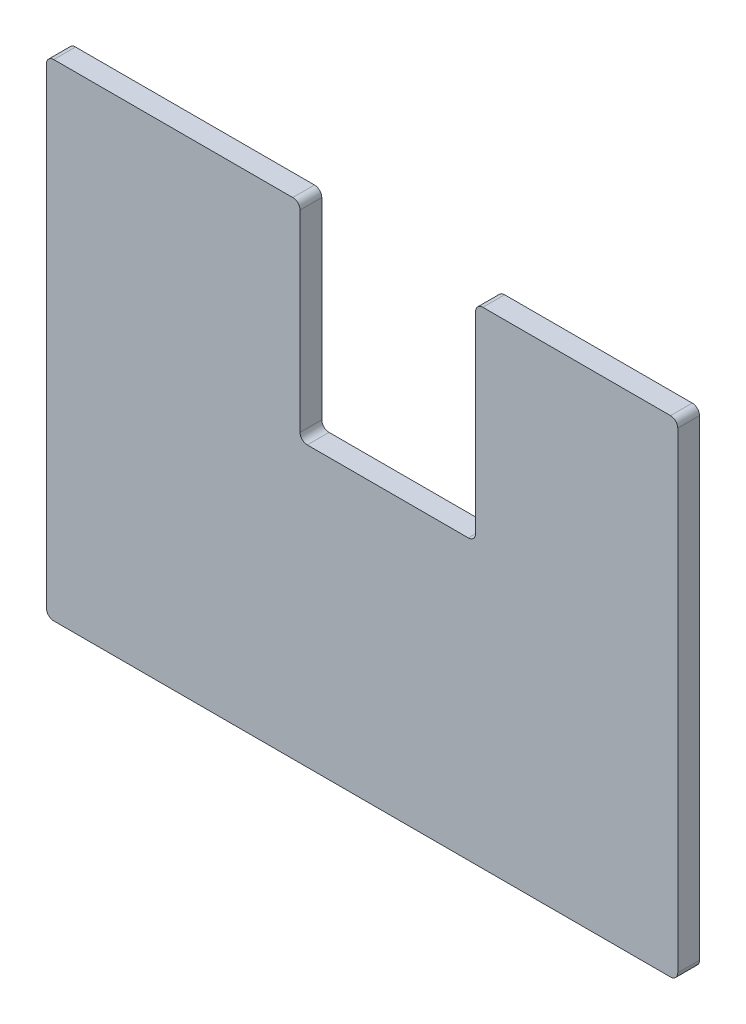
SolidWorks part; units mm, degrees
material "Faia"
ref_plane "Plano frontal" through (0, 0, 0) normal (0, 0, 1) x (1, 0, 0)
ref_plane "Plano superior" through (0, 0, 0) normal (0, 1, 0) x (1, 0, 0)
ref_plane "Plano direito" through (0, 0, 0) normal (1, 0, 0) x (0, 0, -1)
sketch "Esboço1" plane through (0, 0, 0) normal (0, 0, 1) x (1, 0, 0)
  line L0 (65.1024, 0) -> (-63.1564, 0) construction
  line L15 (-43.4857, -30.7684) -> (-43.4857, -35.6299) construction
  line L16 (-8.5074, 33.5098) -> (-43.4857, 33.5098)
  line L17 (43.6082, 33.5098) -> (15.7164, 33.5098)
  line L18 (43.6082, 33.5098) -> (43.6082, -33.5661)
  line L19 (43.6082, -33.5661) -> (-43.4857, -33.5661)
  line L20 (-43.4857, 33.5098) -> (-43.4857, -33.5661)
  line L22 (-8.5074, 33.5098) -> (-8.5074, 4.9536)
  line L23 (-8.5074, 4.9536) -> (15.7164, 4.9536)
  line L24 (15.7164, 33.5098) -> (15.7164, 4.9536)
  line L25 (0, 4.9536) -> (0, -59.4583) construction
extrude "Ressalto-extrusão1" add sketch "Esboço1" along normal blind 3
fillet "Filete1" radius 1 8 edges at (43.6082, -33.5661, 1.5) (-43.4857, -33.5661, 1.5) (-43.4857, 33.5098, 1.5) (-8.5074, 33.5098, 1.5) (15.7164, 4.9536, 1.5) (-8.5074, 4.9536, 1.5) (15.7164, 33.5098, 1.5) (43.6082, 33.5098, 1.5)
